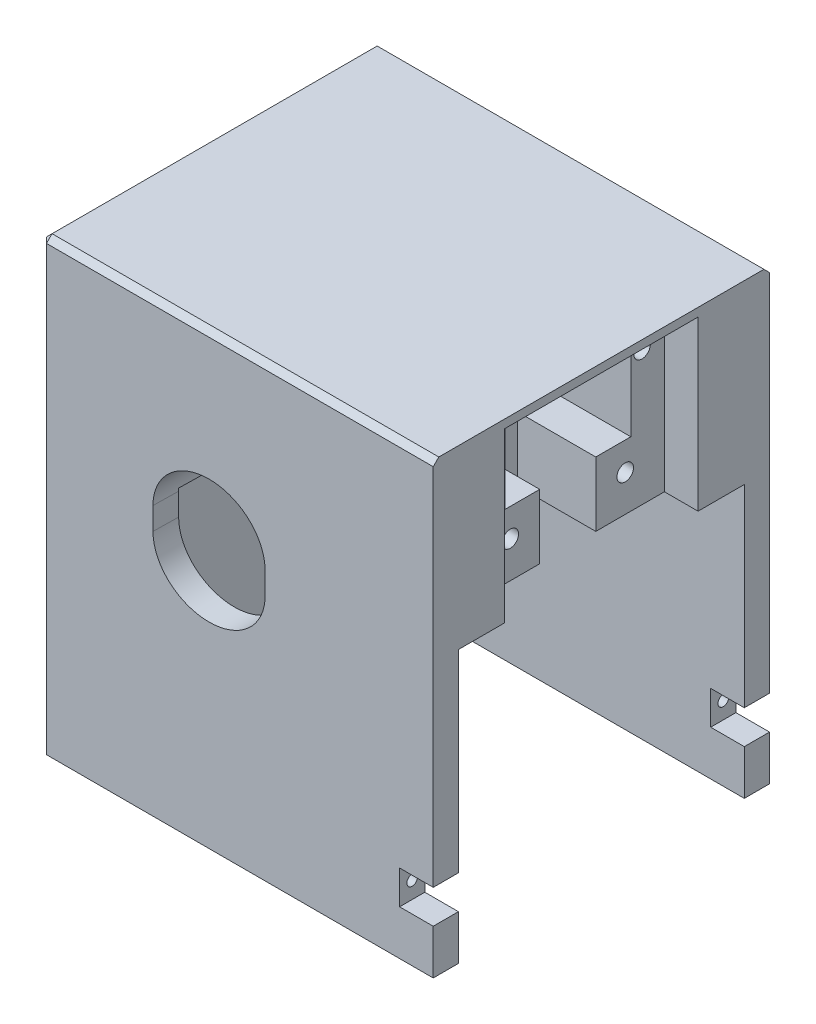
SolidWorks part; units mm, degrees
ref_plane "前视基准面" through (0, 0, 0) normal (0, 0, 1) x (1, 0, 0)
ref_plane "上视基准面" through (0, 0, 0) normal (0, 1, 0) x (1, 0, 0)
ref_plane "右视基准面" through (0, 0, 0) normal (1, 0, 0) x (0, 0, -1)
sketch "草图1" plane through (0, 0, 0) normal (0, 1, 0) x (1, 0, 0)
  line L1 (-35, 30) -> (35, 30)
  line L2 (-35, 30) -> (-35, -30)
  line L3 (-35, -30) -> (35, -30)
  line L4 (35, 30) -> (35, -30)
  line L5 (-35, 30) -> (35, -30) construction
  line L6 (-35, -30) -> (35, 30) construction
  point P0 (0, 0)
  dimension "D1" = 70
  dimension "D2" = 60
extrude "凸台-拉伸1" add sketch "草图1" along normal blind 80
sketch "草图2" plane through (35, 0, 0) normal (1, 0, 0) x (0, 0, -1)
  line L0 (-30, 0) -> (30, 0) construction
  line L1 (-25.5, 0) -> (25.5, 0)
  line L2 (-25.5, 0) -> (-25.5, 48.5)
  line L3 (-25.5, 48.5) -> (25.5, 48.5)
  line L4 (25.5, 0) -> (25.5, 48.5)
  line L5 (-30, 80) -> (-30, 0) construction
  line L6 (30, 80) -> (30, 0) construction
  dimension "D1" = 4.5
  dimension "D2" = 4.5
  dimension "D3" = 48.5
extrude "切除-拉伸1" cut sketch "草图2" against normal offset from surface (65.5 mm away) 4.5 up to face at (-35, 40, 0)
sketch "草图3" plane through (0, 0, 30) normal (0, 0, 1) x (1, 0, 0)
  line L0 (-35, 48) -> (35, 48) construction
  line L1 (-35, 80) -> (-35, 0) construction
  line L2 (35, 80) -> (35, 0) construction
  line L3 (-35, 0) -> (35, 0) construction
  line L4 (23, 80) -> (23, 0) construction
  line L5 (-35, 80) -> (35, 80) construction
  line L8 (-15, 48) -> (-15, 44)
  line L10 (5, 48) -> (5, 44)
  ellipse E0 centre (-5, 48) end of major axis (5, 48) minor radius 9.0909 (5, 48) -> (-15, 48) ccw
  ellipse E1 centre (-5, 44) end of major axis (5, 44) minor radius 9 (-15, 44) -> (5, 44) ccw
  dimension "D1" = 48
  dimension "D2" = 12
  dimension "D3" = 30
  dimension "D4" = 4
extrude "切除-拉伸2" cut sketch "草图3" against normal through all draft 1
sketch "草图4" plane through (35, 0, 0) normal (1, 0, 0) x (0, 0, -1)
  line L0 (-30, 58) -> (30, 58) construction
  line L1 (-30, 80) -> (-30, 0) construction
  line L2 (30, 80) -> (30, 0) construction
  line L3 (25.5, 48.5) -> (-25.5, 48.5) construction
  line L4 (0, 80) -> (0, 0) construction
  line L5 (-30, 80) -> (30, 80) construction
  line L7 (-10.25, 78.5) -> (10.25, 78.5)
  line L8 (-10.25, 78.5) -> (-10.25, 63)
  line L9 (-10.25, 63) -> (10.25, 63)
  line L10 (10.25, 78.5) -> (10.25, 63)
  line L11 (-10.25, 78.5) -> (10.25, 63) construction
  line L12 (-10.25, 63) -> (10.25, 78.5) construction
  point P13 (0, 70.75)
  dimension "D1" = 9.5
  dimension "D2" = 5
  dimension "D3" = 15.5
  dimension "D4" = 20.5
extrude "切除-拉伸3" cut sketch "草图4" against normal blind 41
sketch "草图5" plane through (0, 63, 0) normal (0, 1, 0) x (1, 0, 0)
  line L0 (35, -30) -> (35, 30) construction
  line L1 (-35, -30) -> (35, -30) construction
  circle A0 centre (-6, 0) radius 10
  point P4 (35, 0)
  dimension "D1" = 20
  dimension "D2" = 41
  dimension "D3" = 30
extrude "切除-拉伸4" cut sketch "草图5" against normal blind 21 and the other way blind 15.5
sketch "草图6" plane through (35, 0, 0) normal (1, 0, 0) x (0, 0, -1)
  line L0 (-25.5, 48.5) -> (25.5, 48.5) construction
  line L1 (-5, 34) -> (5, 34)
  line L2 (-5, 34) -> (-5, 63)
  line L3 (-5, 63) -> (5, 63)
  line L4 (5, 34) -> (5, 63)
  line L5 (-5, 34) -> (5, 63) construction
  line L6 (-5, 63) -> (5, 34) construction
  line L7 (-10.25, 63) -> (10.25, 63) construction
  point P0 (0, 48.5)
  dimension "D1" = 10
extrude "切除-拉伸5" cut sketch "草图6" against normal blind 20
sketch "草图7" plane through (35, 0, 0) normal (1, 0, 0) x (0, 0, -1)
  line L0 (-25.5, 48.5) -> (25.5, 48.5) construction
  line L1 (-16.25, 78.5) -> (16.25, 78.5)
  line L2 (-16.25, 78.5) -> (-16.25, 48.5)
  line L3 (-16.25, 48.5) -> (16.25, 48.5)
  line L4 (16.25, 78.5) -> (16.25, 48.5)
  line L5 (-10.25, 78.5) -> (-10.25, 63) construction
  line L6 (10.25, 63) -> (10.25, 78.5) construction
  line L7 (-25.5, 0) -> (-25.5, 48.5) construction
  line L8 (-30, 0) -> (-25.5, 0) construction
  line L9 (25.5, 0) -> (30, 0) construction
  line L10 (30, 80) -> (30, 0) construction
  line L11 (-30, 80) -> (-30, 0) construction
  line L13 (-25.5, 24.25) -> (25.5, 24.25) construction
  line L14 (25.5, 0) -> (25.5, 48.5) construction
  line L15 (0, 48.5) -> (0, 0) construction
  line L20 (30, 8) -> (30, 14)
  line L21 (30, 8) -> (25.5, 8)
  line L22 (25.5, 8) -> (25.5, 14)
  line L23 (30, 14) -> (25.5, 14)
  line L24 (-30, 14) -> (-25.5, 14)
  line L25 (-25.5, 8) -> (-25.5, 14)
  line L26 (-30, 8) -> (-30, 14)
  line L27 (-30, 8) -> (-25.5, 8)
  dimension "D1" = 30
  dimension "D2" = 6
  dimension "D3" = 6
  dimension "D4" = 6
  dimension "D5" = 6
  dimension "D6" = 8
  dimension "D7" = 8
  dimension "D8" = 4.5
  dimension "D9" = 4.5
extrude "切除-拉伸6" cut sketch "草图7" against normal blind 6
sketch "草图8" plane through (-30.5, 0, 0) normal (1, 0, 0) x (0, 0, -1)
  line L0 (-14, 21) -> (-14, 5) construction
  line L1 (-10.5, 21) -> (-10.5, 5)
  line L2 (-17.5, 21) -> (-17.5, 5)
  line L4 (-25.5, 0) -> (-25.5, 48.5) construction
  line L6 (25.5, 0) -> (-25.5, 0) construction
  line L7 (0, 0) -> (0, 48.5) construction
  line L8 (5, 48.5) -> (-5, 48.5) construction
  line L9 (14, 21) -> (14, 5) construction
  line L10 (10.5, 21) -> (10.5, 5)
  line L11 (17.5, 21) -> (17.5, 5)
  arc A0 (-10.5, 21) -> (-17.5, 21) centre (-14, 21) ccw
  arc A1 (-17.5, 5) -> (-10.5, 5) centre (-14, 5) ccw
  arc A2 (10.5, 21) -> (17.5, 21) centre (14, 21) cw
  arc A3 (17.5, 5) -> (10.5, 5) centre (14, 5) cw
  point P2 (-14, 13)
  point P19 (14, 13)
  dimension "D2" = 3.5
  dimension "D1" = 16
  dimension "D3" = 8
  dimension "D4" = 13
sketch "草图13" plane through (0, 63, 0) normal (0, 1, 0) x (1, 0, 0)
  line L0 (35, -30) -> (35, 30) construction
  line L1 (-35, -30) -> (35, -30) construction
  circle A0 centre (-6, 0) radius 11
  dimension "D1" = 22
  dimension "D2" = 41
  dimension "D3" = 30
extrude "切除-拉伸10" cut sketch "草图13" against normal blind 16 and the other way blind 16
sketch "草图14" plane through (29, 0, 0) normal (1, 0, 0) x (0, 0, -1)
  line L0 (-10.25, 78.5) -> (-16.25, 78.5) construction
  line L1 (-11.2327, 78.5) -> (-10.2327, 78.5)
  line L2 (-11.2327, 78.5) -> (-11.2327, 63)
  line L4 (-10.2327, 78.5) -> (-10.2327, 63)
  line L5 (-5, 63) -> (-10.25, 63) construction
  line L6 (10.25, 63) -> (-10.25, 63) construction
  line L8 (10.25, 78.5) -> (11.25, 78.5)
  line L9 (10.25, 78.5) -> (10.25, 63)
  line L11 (11.25, 78.5) -> (11.25, 63)
  line L12 (-10.2327, 63) -> (10.25, 63)
  line L13 (-11.2327, 63) -> (-11.2327, 60)
  line L14 (-11.2327, 60) -> (11.25, 60)
  line L15 (11.25, 63) -> (11.25, 60)
  dimension "D1" = 1
  dimension "D2" = 1
  dimension "D3" = 3
extrude "切除-拉伸7" cut sketch "草图8" against normal through all
sketch "草图9" plane through (29, 0, 0) normal (1, 0, 0) x (0, 0, -1)
  line L0 (-16.25, 78.5) -> (-16.25, 48.5) construction
  line L1 (16.25, 78.5) -> (-16.25, 78.5) construction
  line L2 (-16.25, 48.5) -> (-5, 48.5) construction
  line L4 (0, 80) -> (0, 0) construction
  line L8 (-30, 80) -> (30, 80) construction
  circle A0 centre (-13.25, 72.5) radius 1.475
  circle A1 centre (-10.25, 55) radius 1.475
  circle A6 centre (10.25, 55) radius 1.475
  circle A7 centre (13.25, 72.5) radius 1.475
  dimension "D1" = 2.95
  dimension "D6" = 2.95
  dimension "D2" = 3
  dimension "D3" = 6
  dimension "D4" = 6.5
  dimension "D5" = 6
extrude "切除-拉伸8" cut sketch "草图9" against normal blind 10
chamfer "倒角3" distance 1 angle 45 5 edges at (-35, 40, 30) (-35, 40, -30) (0, 80, -30) (-35, 80, 0) (0, 80, 30)
sketch "草图10" plane through (35, 0, 0) normal (1, 0, 0) x (0, 0, -1)
  line L0 (-25.5, 48.5) -> (25.5, 48.5) construction
  line L1 (-16.25, 78.5) -> (-17.25, 78.5)
  line L2 (-16.25, 78.5) -> (-16.25, 48.5)
  line L3 (-16.25, 48.5) -> (-17.25, 48.5)
  line L4 (-17.25, 78.5) -> (-17.25, 48.5)
  line L6 (16.25, 78.5) -> (17.25, 78.5)
  line L7 (16.25, 78.5) -> (16.25, 48.5)
  line L8 (16.25, 48.5) -> (17.25, 48.5)
  line L9 (17.25, 78.5) -> (17.25, 48.5)
  dimension "D1" = 1
  dimension "D2" = 1
extrude "切除-拉伸9" cut sketch "草图10" against normal blind 6
extrude "切除-拉伸11" cut sketch "草图14" against normal blind 36
sketch "草图15" plane through (29, 0, 0) normal (1, 0, 0) x (0, 0, -1)
  line L0 (-25.5, 0) -> (-25.5, 48.5) construction
  line L6 (-30, 8) -> (-25.5, 8) construction
  line L7 (25.5, 14) -> (25.5, 8) construction
  line L8 (25.5, 8) -> (30, 8) construction
  circle A0 centre (-27.7527, 11) radius 0.95
  circle A1 centre (27.75, 11) radius 0.95
  dimension "D1" = 1.9
  dimension "D5" = 1.9
  dimension "D2" = 2.2527
  dimension "D3" = 3
  dimension "D4" = 2.25
  dimension "D6" = 3
extrude "切除-拉伸12" cut sketch "草图15" against normal blind 5
